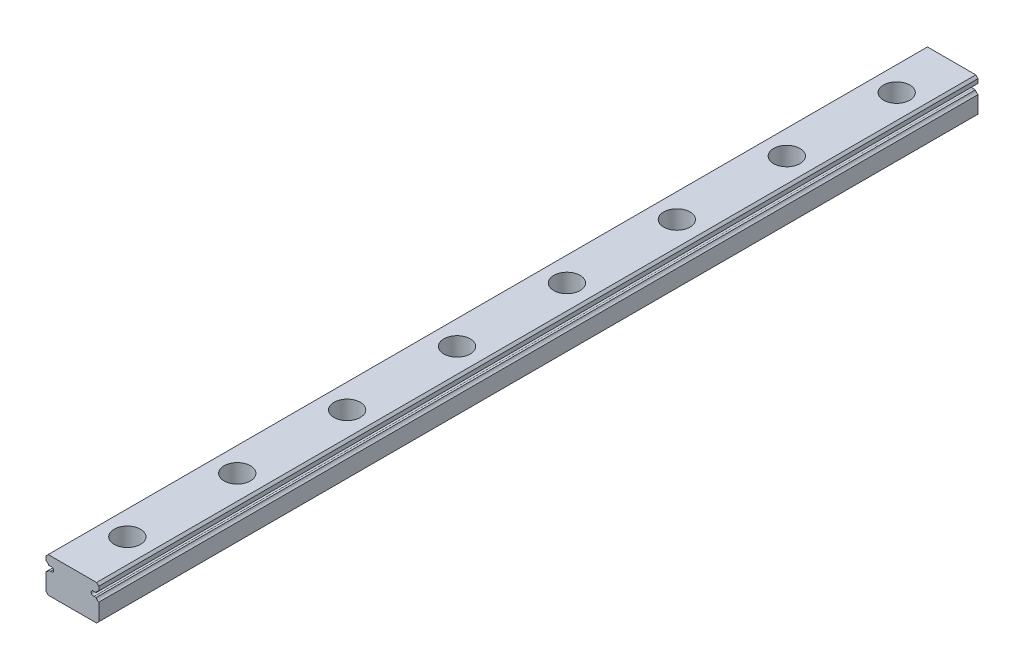
SolidWorks part; units mm, degrees
material "Chrome Stainless Steel"
ref_plane "Front Plane" through (0, 0, 0) normal (0, 0, 1) x (1, 0, 0)
ref_plane "Top Plane" through (0, 0, 0) normal (0, 1, 0) x (1, 0, 0)
ref_plane "Right Plane" through (0, 0, 0) normal (1, 0, 0) x (0, 0, -1)
sketch "Sketch1" plane through (0, 0, 0) normal (0, 0, 1) x (1, 0, 0)
  line L0 (0, 4) -> (0, -4) construction
  line L1 (5.5, -4) -> (-5.5, -4)
  line L2 (-5.5, -4) -> (-6, -3.5)
  line L3 (-6, -3.5) -> (-6, 0.3689)
  line L4 (5.5, 4) -> (-5.5, 4)
  line L5 (-5.5, 4) -> (-6, 3.5)
  line L6 (-6, 2.5511) -> (-6, 3.5)
  line L7 (-5.3839, 0.985) -> (-4.9211, 0.985)
  line L8 (-5.3839, 1.935) -> (-4.9211, 1.935)
  line L9 (5.3839, 0.985) -> (4.9211, 0.985)
  line L10 (5.5, 4) -> (6, 3.5)
  line L11 (6, 2.5511) -> (6, 3.5)
  line L12 (5.3839, 1.935) -> (4.9211, 1.935)
  line L13 (6, -3.5) -> (6, 0.3689)
  line L14 (5.5, -4) -> (6, -3.5)
  circle A0 centre (-6.475, 1.46) radius 1.19 construction
  circle A1 centre (-4.765, 1.46) radius 0.5 construction
  arc A2 (-6, 0.3689) -> (-5.3839, 0.985) centre (-6.475, 1.46) ccw
  arc A3 (-5.3839, 1.935) -> (-6, 2.5511) centre (-6.475, 1.46) ccw
  arc A4 (-4.9211, 0.985) -> (-4.9211, 1.935) centre (-4.765, 1.46) ccw
  arc A5 (5.3839, 1.935) -> (6, 2.5511) centre (6.475, 1.46) cw
  arc A6 (4.9211, 0.985) -> (4.9211, 1.935) centre (4.765, 1.46) cw
  arc A7 (6, 0.3689) -> (5.3839, 0.985) centre (6.475, 1.46) cw
  point P4 (0, 0)
  dimension "D5" = 5.46
  dimension "D6" = 6.475
  dimension "D7" = 2.38
  dimension "D11" = 1
  dimension "D12" = 5.46
  dimension "D13" = 4.765
  dimension "D1" = 8
  dimension "D2" = 0.5
  dimension "D3" = 0.5
  dimension "D4" = 6
  dimension "D8" = 0.5
  dimension "D9" = 0.5
  dimension "D10" = 6
  dimension "D14" = 0.475
  dimension "D15" = 0.475
extrude "Boss-Extrude1" add sketch "Sketch1" along normal blind 200 contours L13 A7 L9 A6 L12 A5 L11 L10 L4 L5 L6 A3 L8 A4 L7 A2 L3 L2 L1 L14
sketch "Sketch2" plane through (0, 4, 0) normal (0, 1, 0) x (1, 0, 0)
  line L0 (5.5, 0) -> (-5.5, 0) construction
  circle A0 centre (0, -12.5) radius 3
  dimension "D1" = 12.5
extrude "Cut-Extrude1" cut sketch "Sketch2" against normal blind 4.5
sketch "Sketch3" plane through (0, -0.5, 0) normal (0, 1, 0) x (1, 0, 0)
  circle A0 centre (0, -12.5) radius 1.75
extrude "Cut-Extrude2" cut sketch "Sketch3" against normal through all
pattern_linear "LPattern1" count 8 spacing 25 along (0, 0, 1) of "Cut-Extrude1", "Cut-Extrude2"
